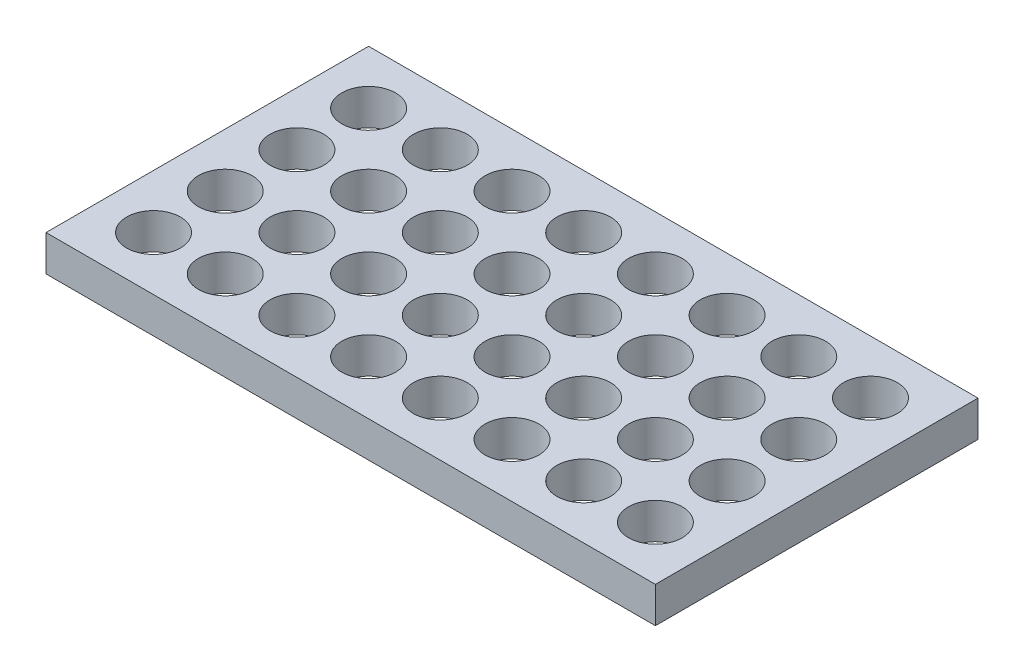
SolidWorks part; units mm, degrees
ref_plane "Front Plane" through (0, 0, 0) normal (0, 0, 1) x (1, 0, 0)
ref_plane "Top Plane" through (0, 0, 0) normal (0, 1, 0) x (1, 0, 0)
ref_plane "Right Plane" through (0, 0, 0) normal (1, 0, 0) x (0, 0, -1)
sketch "Sketch1" plane through (0, 0, 0) normal (0, 1, 0) x (1, 0, 0)
  line L0 (0, 6) -> (6, 6) construction
  line L1 (0, 0) -> (68, 0)
  line L2 (0, 0) -> (0, 36)
  line L3 (0, 36) -> (68, 36)
  line L4 (68, 0) -> (68, 36)
  line L5 (6, 6) -> (6, 0) construction
  line L6 (62, 30) -> (68, 30) construction
  line L7 (62, 30) -> (62, 36) construction
  line L8 (6, 14) -> (6, 6) construction
  circle A0 centre (6, 6) radius 3
  circle A1 centre (14, 6) radius 3
  circle A2 centre (22, 6) radius 3
  circle A3 centre (30, 6) radius 3
  circle A4 centre (38, 6) radius 3
  circle A5 centre (46, 6) radius 3
  circle A6 centre (54, 6) radius 3
  circle A7 centre (62, 6) radius 3
  circle A8 centre (14, 14) radius 3
  circle A9 centre (22, 14) radius 3
  circle A10 centre (30, 14) radius 3
  circle A11 centre (38, 14) radius 3
  circle A12 centre (46, 14) radius 3
  circle A13 centre (54, 14) radius 3
  circle A14 centre (62, 14) radius 3
  circle A15 centre (14, 22) radius 3
  circle A16 centre (22, 22) radius 3
  circle A17 centre (30, 22) radius 3
  circle A18 centre (38, 22) radius 3
  circle A19 centre (46, 22) radius 3
  circle A20 centre (54, 22) radius 3
  circle A21 centre (62, 22) radius 3
  circle A22 centre (14, 30) radius 3
  circle A23 centre (22, 30) radius 3
  circle A24 centre (30, 30) radius 3
  circle A25 centre (38, 30) radius 3
  circle A26 centre (46, 30) radius 3
  circle A27 centre (54, 30) radius 3
  circle A28 centre (62, 30) radius 3
  circle A29 centre (6, 14) radius 3
  circle A30 centre (6, 22) radius 3
  circle A31 centre (6, 30) radius 3
  point P8 (7.1463, 15.1463)
  point P74 (14.8987, 14.8987)
  dimension "D1" = 6
  dimension "D2" = 8
  dimension "D3" = 8
  dimension "D6" = 6
  dimension "D4" = 8
  dimension "D5" = 4
extrude "Boss-Extrude1" add sketch "Sketch1" along normal blind 4
